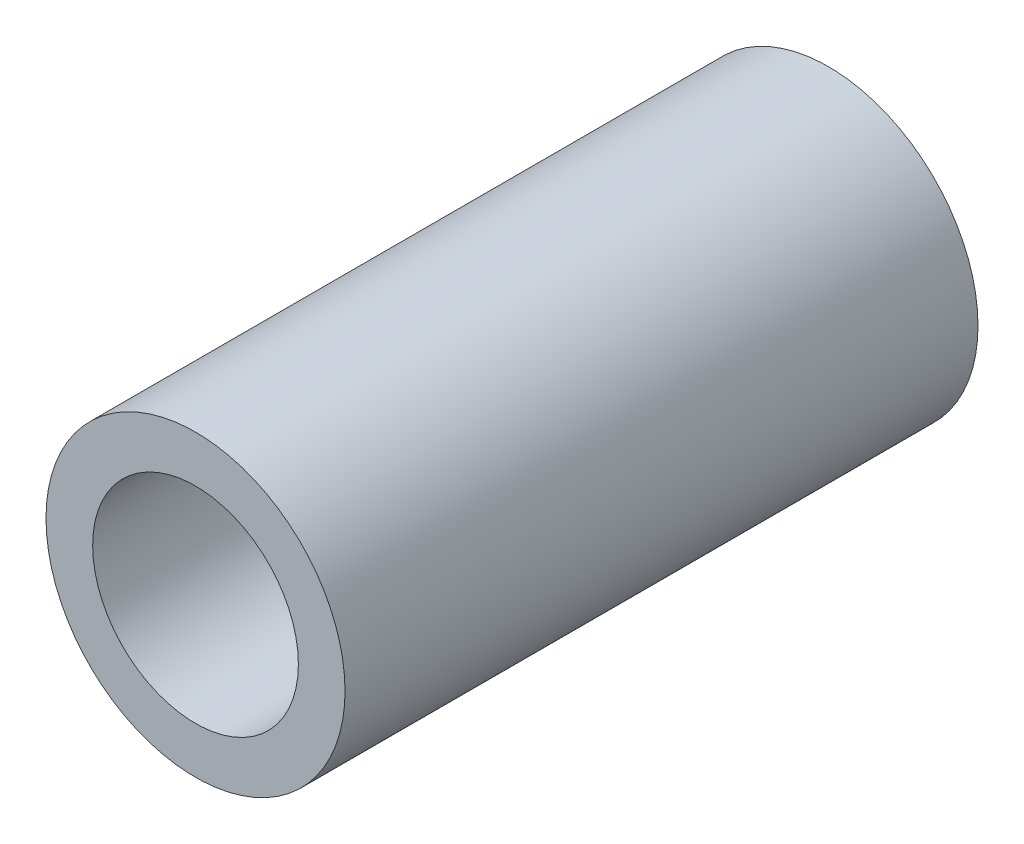
SolidWorks part; units mm, degrees
ref_plane "Front Plane" through (0, 0, 0) normal (0, 0, 1) x (1, 0, 0)
ref_plane "Top Plane" through (0, 0, 0) normal (0, 1, 0) x (1, 0, 0)
ref_plane "Right Plane" through (0, 0, 0) normal (1, 0, 0) x (0, 0, -1)
sketch "Sketch1" plane through (0, 0, 0) normal (0, 0, 1) x (1, 0, 0)
  circle A0 centre (0, 0) radius 6
  circle A1 centre (0, 0) radius 4.1277
  dimension "D1" = 12
extrude "Boss-Extrude1" add sketch "Sketch1" against normal mid plane 25.4
